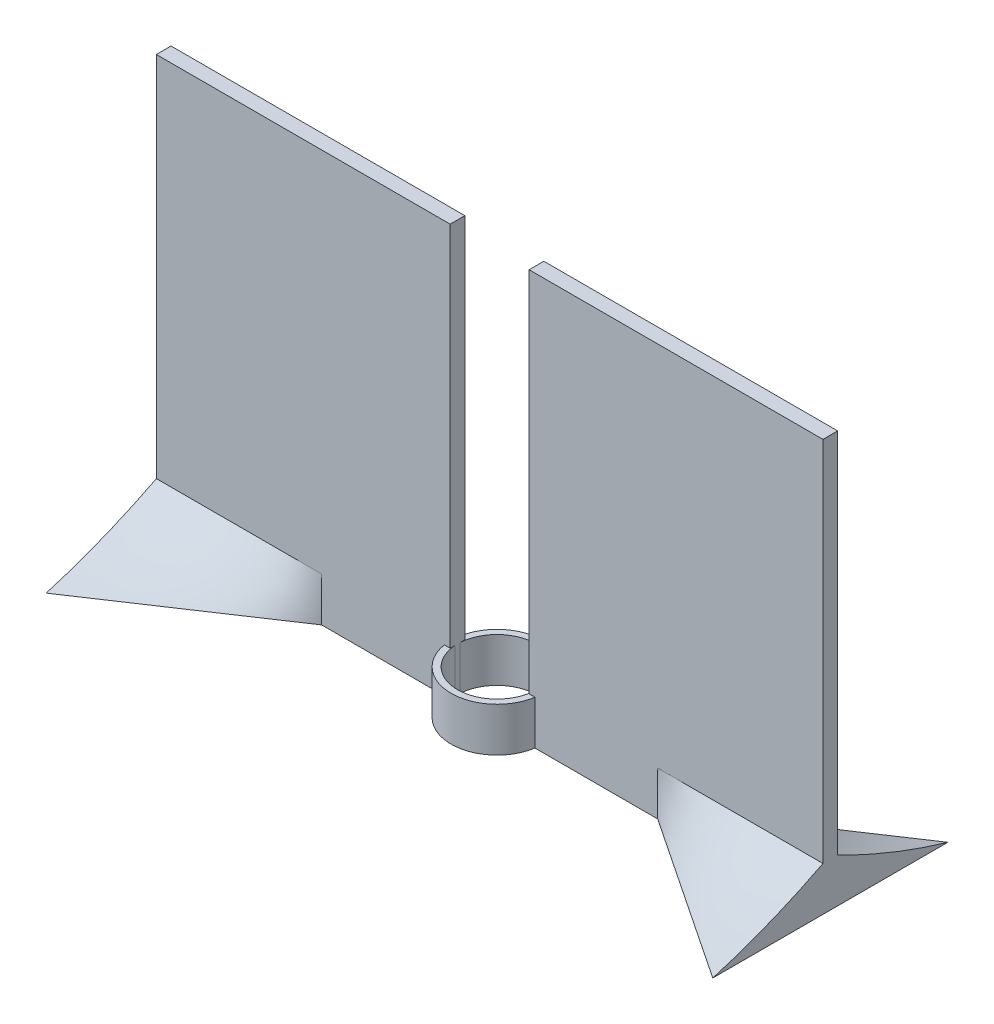
SolidWorks part; units mm, degrees
ref_plane "Front Plane" through (0, 0, 0) normal (0, 0, 1) x (1, 0, 0)
ref_plane "Top Plane" through (0, 0, 0) normal (0, 1, 0) x (1, 0, 0)
ref_plane "Right Plane" through (0, 0, 0) normal (1, 0, 0) x (0, 0, -1)
ref_plane "Plane1" through (10.75, 0, 0) normal (1, 0, 0) x (0, 0, -1)
ref_plane "Plane2" through (120, 0, 0) normal (1, 0, 0) x (0, 0, -1)
sketch "Sketch1" plane through (10.75, 0, 0) normal (1, 0, 0) x (0, 0, -1)
  line L0 (0, 0) -> (0, 12)
  line L1 (0, 55) -> (0, -55) construction
  line L2 (0, 12) -> (0, 112)
  line L3 (0, 112) -> (2, 112)
  line L4 (0, 112) -> (-2, 112)
  line L6 (2, 112) -> (-2, 112)
  line L7 (2, 112) -> (2, 12)
  line L8 (2, 12) -> (-2, 12)
  line L9 (-2, 112) -> (-2, 12)
  line L10 (2, 12) -> (-2, 12)
  line L11 (2, 12) -> (2, 0)
  line L12 (2, 0) -> (-2, 0)
  line L13 (-2, 12) -> (-2, 0)
  dimension "D1" = 100
  dimension "D2" = 4
  dimension "D3" = 12
extrude "Boss-Extrude1" add sketch "Sketch1" along normal blind 80 contours L7 L6 L9 L8
sketch "Sketch5" plane through (90.75, 0, 0) normal (1, 0, 0) x (0, 0, -1)
  line L0 (2, 112) -> (2, 12) construction
  line L1 (-2, 12) -> (2, 12)
  line L6 (-32, 0) -> (32, 0)
  spline S0 degree 2 poles (-2, 12) (-16.4384, 4.5614) (-32, 0) knots 0 0 0 1 1 1
  spline S1 degree 2 poles (2, 12) (16.4384, 4.5614) (32, 0) knots 0 0 0 1 1 1
  dimension "D2" = 4
  dimension "D3" = 30
  dimension "D1" = 30
sketch "Sketch6" plane through (10.75, 0, 0) normal (-1, 0, 0) x (0, 0, 1)
  line L3 (-2, 12) -> (2, 12)
  line L4 (-2, 12) -> (-2, 0)
  line L5 (-2, 0) -> (2, 0)
  line L6 (2, 12) -> (2, 0)
  dimension "D1" = 12
ref_plane "Plane3" through (45.75, 0, 0) normal (1, 0, 0) x (0, 0, -1)
sketch "Sketch7" plane through (45.75, 0, 0) normal (1, 0, 0) x (0, 0, -1)
  line L1 (-2, 12) -> (2, 12)
  line L2 (-2, 12) -> (-2, 0)
  line L3 (-2, 0) -> (2, 0)
  line L4 (2, 12) -> (2, 0)
extrude "Boss-Extrude2" add sketch "Sketch6" against normal up to vertex (35 mm away) contours L6 L5 L4 L3 up to point (45.75, 0, -2)
loft "Loft3" add profiles "Sketch7", "Sketch5"
mirror "Mirror3" about plane through (0, 0, 0) normal (1, 0, 0) of bodies 105
sketch "Sketch14" plane through (0, 0, 0) normal (0, 1, 0) x (1, 0, 0)
  circle A0 centre (0, 0) radius 10.775
  circle A1 centre (0, 0) radius 12.5
  dimension "D1" = 21.55
  dimension "D2" = 25
extrude "Boss-Extrude3" add sketch "Sketch14" along normal blind 12
equation "\"D1@Sketch5\"=\"D3@Sketch5\""
